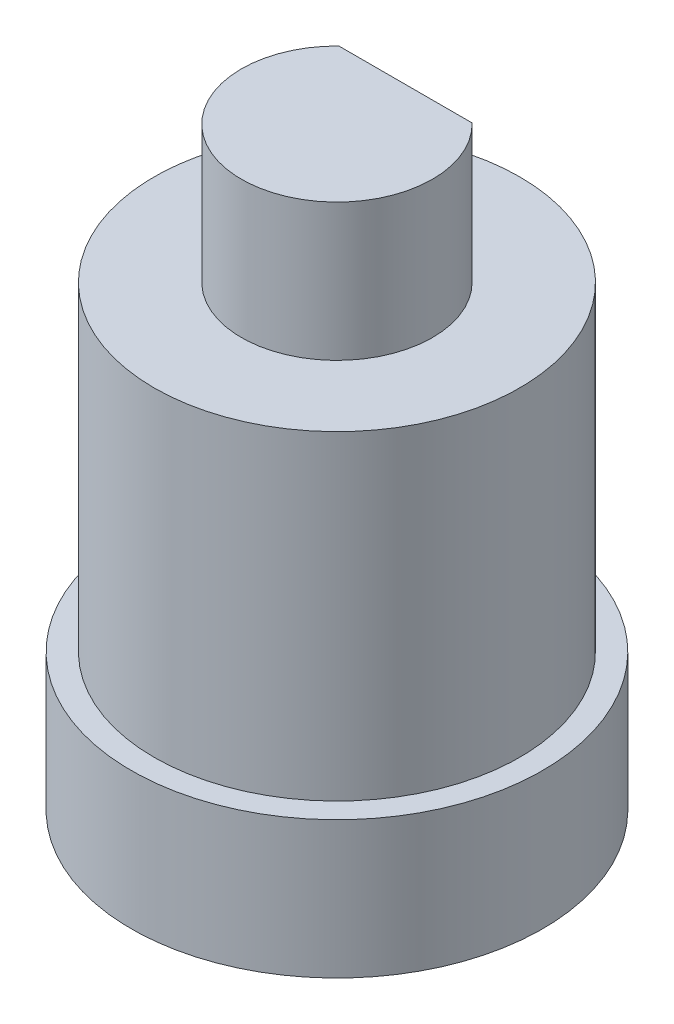
SolidWorks part; units mm, degrees
ref_plane "Front Plane" through (0, 0, 0) normal (0, 0, 1) x (1, 0, 0)
ref_plane "Top Plane" through (0, 0, 0) normal (0, 1, 0) x (1, 0, 0)
ref_plane "Right Plane" through (0, 0, 0) normal (1, 0, 0) x (0, 0, -1)
sketch "Sketch1" plane through (0, 0, 0) normal (0, 1, 0) x (1, 0, 0)
  circle A0 centre (0, 0) radius 4
  dimension "D1" = 8
extrude "Boss-Extrude1" add sketch "Sketch1" along normal blind 10
sketch "Sketch2" plane through (0, 10, 0) normal (0, 1, 0) x (1, 0, 0)
  line L0 (-1.4576, 1.5) -> (1.4576, 1.5)
  circle A0 centre (0, 0) radius 2.0916
  dimension "D1" = 4.1831
  dimension "D2" = 1.5
extrude "Boss-Extrude2" add sketch "Sketch2" along normal blind 3 contours L0 A0
sketch "Sketch3" plane through (0, 0, 0) normal (0, -1, 0) x (1, 0, 0)
  circle A0 centre (0, 0) radius 4.5
  circle A1 centre (0, 0) radius 4
  circle A2 centre (0, 0) radius 4
  dimension "D2" = 9
  dimension "D1" = 0
extrude "Boss-Extrude3" add sketch "Sketch3" against normal blind 3
